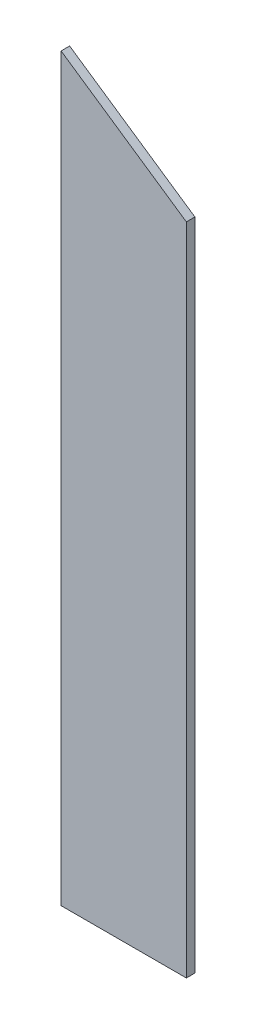
SolidWorks part; units mm, degrees
ref_plane "Plano frontal" through (0, 0, 0) normal (0, 0, 1) x (1, 0, 0)
ref_plane "Plano superior" through (0, 0, 0) normal (0, 1, 0) x (1, 0, 0)
ref_plane "Plano direito" through (0, 0, 0) normal (1, 0, 0) x (0, 0, -1)
sketch "Esboço1" plane through (0, 0, 0) normal (0, 0, 1) x (1, 0, 0)
  line L2 (-110, 650) -> (-110, -650)
  line L3 (-110, -650) -> (110, -650)
  line L4 (110, 500) -> (110, -650)
  line L5 (-110, 650) -> (110, -650) construction
  line L6 (-110, -650) -> (87.2414, 515.5172) construction
  line L7 (110, 500) -> (-110, 650)
  point P0 (0, 0)
  dimension "D1" = 220
  dimension "D2" = 1300
  dimension "D3" = 1150
extrude "Ressalto-extrusão1" add sketch "Esboço1" along normal blind 15
